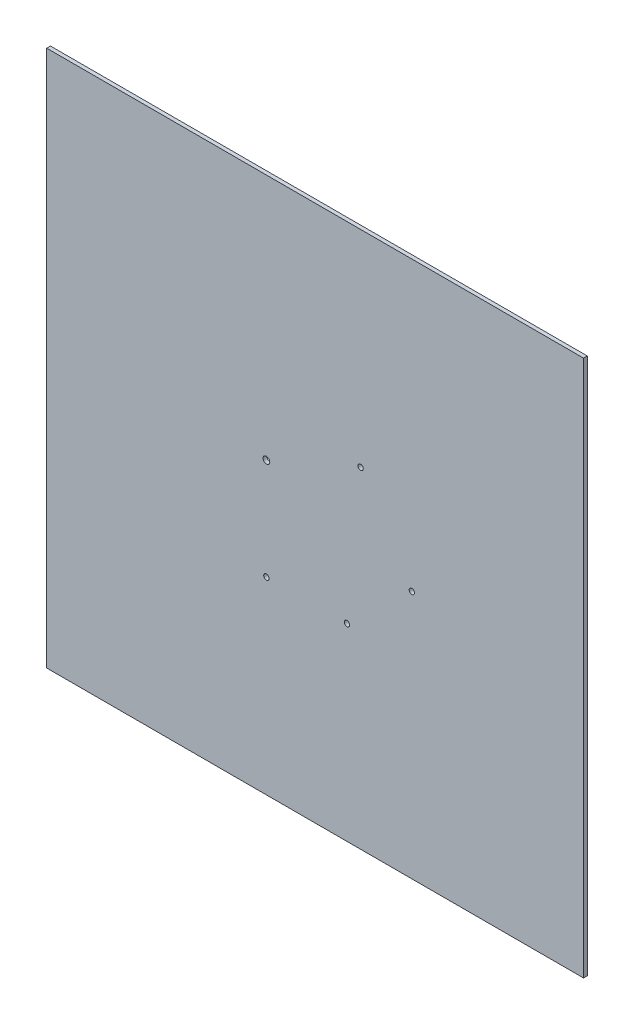
SolidWorks part; units mm, degrees
material "Cedar"
ref_plane "Front Plane" through (0, 0, 0) normal (0, 0, 1) x (1, 0, 0)
ref_plane "Top Plane" through (0, 0, 0) normal (0, 1, 0) x (1, 0, 0)
ref_plane "Right Plane" through (0, 0, 0) normal (1, 0, 0) x (0, 0, -1)
sketch "Sketch2" plane through (0, 0, 0) normal (0, 0, 1) x (1, 0, 0)
  line L1 (401.8817, -319.4711) -> (-233.1183, -319.4711)
  line L2 (401.8817, -319.4711) -> (401.8817, 315.5289)
  line L3 (401.8817, 315.5289) -> (-233.1183, 315.5289)
  line L4 (-233.1183, -319.4711) -> (-233.1183, 315.5289)
  line L5 (401.8817, -319.4711) -> (-233.1183, 315.5289) construction
  line L6 (401.8817, 315.5289) -> (-233.1183, -319.4711) construction
  point P0 (41.2053, 41.2053)
  dimension "D1" = 635
  dimension "D2" = 635
extrude "Boss-Extrude3" add sketch "Sketch2" along normal blind 4.445
sketch "Sketch3" plane through (0, 0, 0) normal (0, 0, -1) x (-1, 0, 0)
  circle A0 centre (-138.1432, 71.8714) radius 3.175
  circle A1 centre (-198.8095, -25.0001) radius 3.175
  circle A2 centre (-122.0047, -96.2659) radius 3.175
  circle A3 centre (-26.7547, -96.2659) radius 3.175
  circle A4 centre (-26.7547, 23.4697) radius 3.9751
  dimension "D1" = 6.35
  dimension "D2" = 6.35
  dimension "D3" = 6.35
  dimension "D4" = 6.35
  dimension "D5" = 7.9502
extrude "Cut-Extrude1" cut sketch "Sketch3" against normal through all
sketch "Sketch4" plane through (0, 0, 4.445) normal (0, 0, 1) x (1, 0, 0)
  line L0 (43.2524, -86.7409) -> (105.5069, -86.7409)
  line L1 (43.2524, -105.7909) -> (105.5069, -105.7909)
  line L2 (180.2372, -29.2393) -> (127.6196, -78.0622)
  line L3 (193.1946, -43.2038) -> (140.577, -92.0267)
  line L4 (154.9723, 62.9447) -> (198.1257, -5.9624)
  line L5 (138.827, 52.8336) -> (181.9805, -16.0735)
  line L6 (17.2297, 6.9719) -> (17.2297, -79.7681)
  line L7 (36.2797, 6.9719) -> (36.2797, -79.7681)
  line L8 (38.0897, 38.7805) -> (119.2162, 74.0324)
  line L9 (45.6817, 21.3087) -> (126.8082, 56.5606)
  line L10 (19.1626, 40.9415) -> (130.5512, 89.3432) construction
  line L11 (154.2884, 81.9824) -> (214.9548, -14.8891) construction
  line L12 (211.767, -38.9646) -> (134.9621, -110.2304) construction
  line L13 (121.0912, 63.3784) -> (27.9256, -77.2519)
  line L14 (154.0243, 61.3503) -> (42.6358, -106.7869) construction
  line L15 (136.9723, 52.8574) -> (43.8067, -87.7729)
  line L16 (31.9202, 41.806) -> (203.9751, -6.6638) construction
  line L17 (45.2171, 28.1644) -> (185.5126, -11.3585)
  line L18 (40.0516, 9.8281) -> (180.3471, -29.6948)
  line L19 (109.0291, -82.3182) -> (76.3447, 34.6327)
  line L20 (127.6196, -78.0622) -> (93.9827, 42.2969)
  line L21 (117.635, -77.7238) -> (85.1637, 38.4648) construction
  line L22 (-233.1183, 315.5289) -> (401.8817, 315.5289)
  line L23 (-233.1183, 315.5289) -> (-233.1183, -319.4711)
  line L24 (401.8817, 315.5289) -> (401.8817, -319.4711)
  line L25 (-233.1183, -319.4711) -> (401.8817, -319.4711)
  line L26 (-233.1183, -319.4711) -> (401.8817, -319.4711) construction
  line L27 (-64.6976, -86.7409) -> (10.2569, -86.7409)
  line L28 (-64.6976, -105.7909) -> (10.2569, -105.7909)
  line L29 (-95.344, -83.5098) -> (12.606, 36.2258) construction
  line L30 (-77.2226, -77.6347) -> (8.6332, 17.5946)
  line L31 (22.782, 4.8386) -> (-63.0739, -90.3908)
  line L32 (138.5024, -105.7909) -> (283.3069, -105.7909)
  line L33 (138.5024, -86.7409) -> (283.3069, -86.7409)
  line L34 (209.7928, -9.4351) -> (310.7879, -80.7008) construction
  line L35 (217.7809, -26.7294) -> (291.8166, -78.9716)
  line L36 (206.7976, -42.2944) -> (280.8333, -94.5366)
  line L37 (-64.6976, 32.9947) -> (10.2569, 32.9947)
  line L38 (-64.6976, 13.9447) -> (10.2569, 13.9447)
  line L39 (-90.7203, 6.9719) -> (-90.7203, -79.7681)
  line L40 (-71.6703, 6.9719) -> (-71.6703, -79.7681)
  line L41 (-62.2683, 21.3087) -> (26.5594, -77.2169)
  line L42 (-73.9731, 5.8419) -> (9.9667, -87.2621)
  line L43 (-95.344, 10.7137) -> (12.606, -109.0219) construction
  circle A0 centre (26.7547, 23.4697) radius 19.05
  circle A1 centre (138.1432, 71.8714) radius 19.05
  circle A2 centre (198.8095, -25.0001) radius 19.05
  circle A3 centre (122.0047, -96.2659) radius 19.05
  circle A4 centre (26.7547, -96.2659) radius 19.05
  circle A5 centre (299.8047, -96.2659) radius 19.05
  circle A6 centre (299.8047, -96.2659) radius 3.175
  circle A7 centre (-81.1953, -96.2659) radius 19.05
  circle A8 centre (-81.1953, -96.2659) radius 3.175
  circle A9 centre (26.7547, -96.2659) radius 3.175 construction
  circle A10 centre (-81.1953, 23.4697) radius 3.9751
  circle A11 centre (-81.1953, 23.4697) radius 19.05
  circle A12 centre (26.7547, 23.4697) radius 3.9751 construction
  point P55 (97.706, -6.4138)
  line M6 (-233.1183, 315.5289) -> (-233.1183, -319.4711)
  line M7 (-233.1183, -319.4711) -> (401.8817, -319.4711)
  line M8 (401.8817, -319.4711) -> (401.8817, 315.5289)
  line M9 (401.8817, 315.5289) -> (-233.1183, 315.5289)
  dimension "D1" = 38.1
  dimension "D2" = 19.05
  dimension "D3" = 19.05
  dimension "D4" = 19.05
  dimension "D5" = 19.05
  dimension "D6" = 19.05
  dimension "D7" = 19.05
  dimension "D8" = 19.05
  dimension "D9" = 19.05
  dimension "D10" = 9.525
  dimension "D11" = 203.2
  dimension "D12" = 177.8
  dimension "D13" = 19.05
  dimension "D14" = 19.05
  dimension "D15" = 19.05
  dimension "D16" = 19.05
  dimension "D17" = 19.05
  dimension "D18" = 19.05
  dimension "D19" = 19.05
extrude "Cut-Extrude2" [suppressed] cut sketch "Sketch4" against normal through all contours A4 L6 A0 L8 A1 L4 A2 L3 A3 L1 M9 M6 M7 M8 | A0 L7 L13 L18 | A3 L19 L15 L0 | L20 L2 L18 | A1 L15 L17 L5 | L20 L13 L9 | L17 L19 L9 | A4 L6 L31 L27 | A8 | A6 | A2 L3 L33 L36
